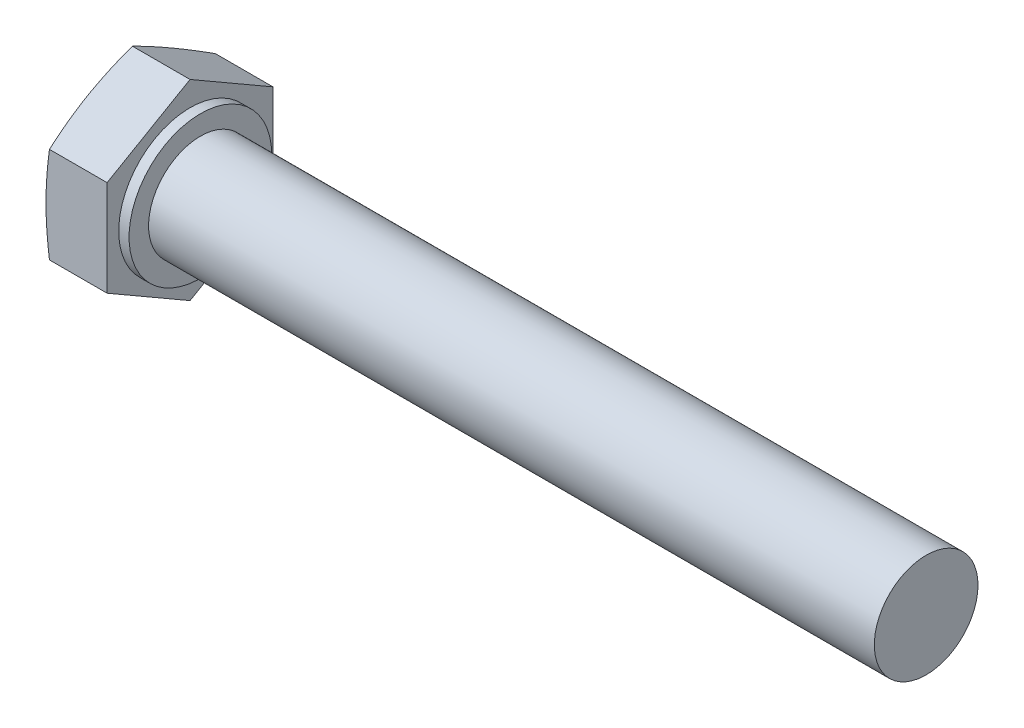
SolidWorks part; units mm, degrees
ref_plane "Спереди" through (0, 0, 0) normal (0, 0, 1) x (1, 0, 0)
ref_plane "Сверху" through (0, 0, 0) normal (0, 1, 0) x (1, 0, 0)
ref_plane "Справа" through (0, 0, 0) normal (1, 0, 0) x (0, 0, -1)
sketch "Sk1" plane through (0, 0, 0) normal (1, 0, 0) x (0, 0, -1)
  line L1 (0, 4.6188) -> (-4, 2.3094)
  line L2 (-4, 2.3094) -> (-4, -2.3094)
  line L3 (-4, -2.3094) -> (0, -4.6188)
  line L4 (0, -4.6188) -> (4, -2.3094)
  line L5 (4, -2.3094) -> (4, 2.3094)
  line L6 (4, 2.3094) -> (0, 4.6188)
  circle A0 centre (0, 0) radius 4 construction
  dimension "s" = 8
extrude "Head" add sketch "Sk1" against normal blind 3.5
sketch "Sk2" plane through (0, 0, 0) normal (0, 0, 1) x (1, 0, 0)
  line L0 (-0.1, 3.44) -> (-0.1, -6.5241) construction
  line L1 (0, 2.3094) -> (0, -2.3094) construction
  line L2 (-0.5, 3.44) -> (0, 3.44)
  line L3 (0, 0) -> (-8.3676, 0) construction
  line L4 (0, 4.6188) -> (0, 2.3094) construction
  line L5 (-0.5, 3.44) -> (-0.5, 4.6188)
  line L6 (-3.5, 4.6188) -> (0, 4.6188) construction
  line L7 (-0.5, 4.6188) -> (0, 4.6188)
  line L8 (0, 4.6188) -> (0, 3.44)
  dimension "D1" = 0.1
  dimension "dw" = 6.88
  dimension "c" = 0.5
revolve "UNHead" cut sketch "Sk2" angle 360 about L3
sketch "Sk3" plane through (0, 0, 0) normal (1, 0, 0) x (0, 0, -1)
  circle A0 centre (0, 0) radius 2.5
  dimension "d" = 5
extrude "Body" add sketch "Sk3" along normal blind 35
cosmetic thread "Thrd" parameters "Lr"=16, "dr"=4.134
sketch "Sk5" plane through (-3.5, 0, 0) normal (-1, 0, 0) x (0, 0, 1)
  circle A0 centre (0, 0) radius 3.8
  dimension "D1" = 7.6
extrude "HeadChamfer" cut sketch "Sk5" against normal through all draft 75 flip side to cut
sketch "NoToCut" plane through (0, 0, 0) normal (0, 0, 1) x (1, 0, 0)
  line L0 (19, 2.5) -> (19, -2.5)
  line L1 (35, 2.5) -> (0, 2.5) construction
  line L2 (0, -2.5) -> (35, -2.5) construction
  line L3 (0, -3.44) -> (0, 3.44) construction
sketch "Sk4" plane through (0, 0, 0) normal (0, 0, 1) x (1, 0, 0)
  line L0 (0, 0) -> (16.5214, 0) construction
  line L2 (0, -3.44) -> (0, 3.44) construction
  line L3 (35, 2.5) -> (0, 2.5) construction
  line L4 (0.35, 2.5) -> (0, 2.5)
  line L5 (0, 2.5) -> (0, 2.85)
  arc A0 (0, 2.85) -> (0.35, 2.5) centre (0.35, 2.85) ccw
  dimension "r" = 0.35
  dimension "da" = 5.7
revolve "Fillet" [suppressed] add sketch "Sk4" angle 360 about L0
chamfer "Cham" [suppressed] distance 0.6 angle 45
equation "\"D1@Sk5\" = .95 * \"s@Sk1\""
equation "\"Lr@Thrd\" = \"l@Body\" - \"Lg@NoToCut\""
